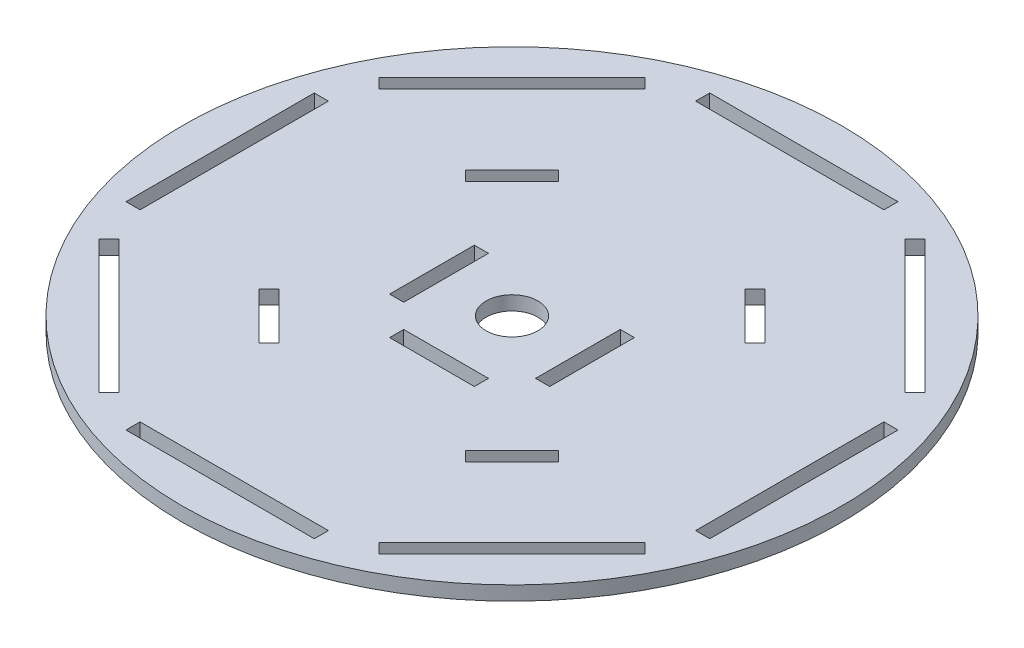
SolidWorks part; units mm, degrees
ref_plane "Alzado" through (0, 0, 0) normal (0, 0, 1) x (1, 0, 0)
ref_plane "Planta" through (0, 0, 0) normal (0, 1, 0) x (1, 0, 0)
ref_plane "Vista lateral" through (0, 0, 0) normal (1, 0, 0) x (0, 0, -1)
sketch "Croquis1" plane through (0, 0, 0) normal (0, 1, 0) x (1, 0, 0)
  line L0 (24.7487, 24.7487) -> (29.6985, 19.799)
  line L1 (29.6985, 19.799) -> (31.8198, 21.9203)
  line L2 (31.8198, 21.9203) -> (21.9203, 31.8198)
  line L3 (19.799, 29.6985) -> (21.9203, 31.8198)
  line L4 (24.7487, 24.7487) -> (19.799, 29.6985)
  line L5 (24.7487, -24.7487) -> (19.799, -29.6985)
  line L6 (19.799, -29.6985) -> (21.9203, -31.8198)
  line L7 (21.9203, -31.8198) -> (31.8198, -21.9203)
  line L8 (29.6985, -19.799) -> (31.8198, -21.9203)
  line L9 (24.7487, -24.7487) -> (29.6985, -19.799)
  line L10 (0, 0) -> (-24.7487, 24.7487) construction
  line L11 (-24.7487, 24.7487) -> (-19.799, 29.6985)
  line L12 (-19.799, 29.6985) -> (-21.9203, 31.8198)
  line L13 (-24.7487, -24.7487) -> (-29.6985, -19.799)
  line L14 (-29.6985, -19.799) -> (-31.8198, -21.9203)
  line L15 (-31.8198, -21.9203) -> (-21.9203, -31.8198)
  line L16 (-19.799, -29.6985) -> (-21.9203, -31.8198)
  line L17 (-24.7487, -24.7487) -> (-19.799, -29.6985)
  line L19 (-14, 0) -> (-14, 9)
  line L20 (-14, 9) -> (-17, 9)
  line L21 (-17, 9) -> (-17, -9)
  line L22 (-17, -9) -> (-14, -9)
  line L23 (-21.9203, 31.8198) -> (-31.8198, 21.9203)
  line L24 (-24.7487, 24.7487) -> (-29.6985, 19.799)
  line L25 (-29.6985, 19.799) -> (-31.8198, 21.9203)
  line L26 (-14, -9) -> (-14, 0)
  line L31 (0, 0) -> (24.7487, 24.7487) construction
  line L32 (14, 0) -> (14, -9)
  line L33 (14, -9) -> (17, -9)
  line L34 (17, -9) -> (17, 9)
  line L35 (17, 9) -> (14, 9)
  line L36 (14, 9) -> (14, 0)
  line L37 (0, 0) -> (24.7487, -24.7487) construction
  line L38 (0, -14) -> (-9, -14)
  line L39 (-9, -14) -> (-9, -17)
  line L40 (-9, -17) -> (9, -17)
  line L41 (0, 0) -> (0, 62) construction
  line L42 (0, 62) -> (20, 62)
  line L43 (20, 62) -> (20, 59)
  line L44 (20, 59) -> (-20, 59)
  line L45 (-20, 59) -> (-20, 62)
  line L46 (-20, 62) -> (0, 62)
  line L47 (55.8614, 27.5772) -> (27.5772, 55.8614)
  line L48 (27.5772, 55.8614) -> (29.6985, 57.9828)
  line L49 (29.6985, 57.9828) -> (43.8406, 43.8406)
  line L50 (43.8406, 43.8406) -> (57.9828, 29.6985)
  line L51 (57.9828, 29.6985) -> (55.8614, 27.5772)
  line L52 (59, -20) -> (59, 20)
  line L53 (59, 20) -> (62, 20)
  line L54 (62, 20) -> (62, 0)
  line L55 (62, 0) -> (62, -20)
  line L56 (62, -20) -> (59, -20)
  line L57 (27.5772, -55.8614) -> (55.8614, -27.5772)
  line L58 (55.8614, -27.5772) -> (57.9828, -29.6985)
  line L59 (57.9828, -29.6985) -> (43.8406, -43.8406)
  line L60 (43.8406, -43.8406) -> (29.6985, -57.9828)
  line L61 (29.6985, -57.9828) -> (27.5772, -55.8614)
  line L62 (-20, -59) -> (20, -59)
  line L63 (20, -59) -> (20, -62)
  line L64 (20, -62) -> (0, -62)
  line L65 (0, -62) -> (-20, -62)
  line L66 (-20, -62) -> (-20, -59)
  line L67 (-55.8614, -27.5772) -> (-27.5772, -55.8614)
  line L68 (-27.5772, -55.8614) -> (-29.6985, -57.9828)
  line L69 (-29.6985, -57.9828) -> (-43.8406, -43.8406)
  line L70 (-43.8406, -43.8406) -> (-57.9828, -29.6985)
  line L71 (-57.9828, -29.6985) -> (-55.8614, -27.5772)
  line L72 (-59, 20) -> (-59, -20)
  line L73 (-59, -20) -> (-62, -20)
  line L74 (-62, -20) -> (-62, 0)
  line L75 (-62, 0) -> (-62, 20)
  line L76 (-62, 20) -> (-59, 20)
  line L77 (-27.5772, 55.8614) -> (-55.8614, 27.5772)
  line L78 (-55.8614, 27.5772) -> (-57.9828, 29.6985)
  line L79 (-57.9828, 29.6985) -> (-43.8406, 43.8406)
  line L80 (-43.8406, 43.8406) -> (-29.6985, 57.9828)
  line L81 (-29.6985, 57.9828) -> (-27.5772, 55.8614)
  line L82 (9, -17) -> (9, -14)
  line L83 (9, -14) -> (0, -14)
  line L84 (0, 0) -> (-24.7487, -24.7487) construction
  line L86 (0, 14) -> (9, 14) [skipped]
  line L87 (9, 14) -> (9, 17) [skipped]
  line L88 (9, 17) -> (-9, 17) [skipped]
  line L89 (-9, 17) -> (-9, 14) [skipped]
  line L90 (-9, 14) -> (0, 14) [skipped]
  circle A0 centre (0, 0) radius 5.5
  circle A2 centre (0, 0) radius 70
  point P26 (0, 0)
  point P47 (0, 0)
  point P88 (0, 0)
  point P93 (0, 0)
  dimension "D2" = 7
  dimension "D3" = 140
  dimension "D12" = 11
  dimension "D4" = 35
  dimension "D5" = 4
  dimension "D6" = 4
  dimension "D7" = 9
  dimension "D8" = 3
  dimension "D9" = 7
  dimension "D10" = 3
  dimension "D11" = 18
  dimension "D15" = 20
  dimension "D16" = 3
  dimension "D17" = 40
  dimension "D18" = 8
extrude "Saliente-Extruir1" add sketch "Croquis1" along normal blind 3
